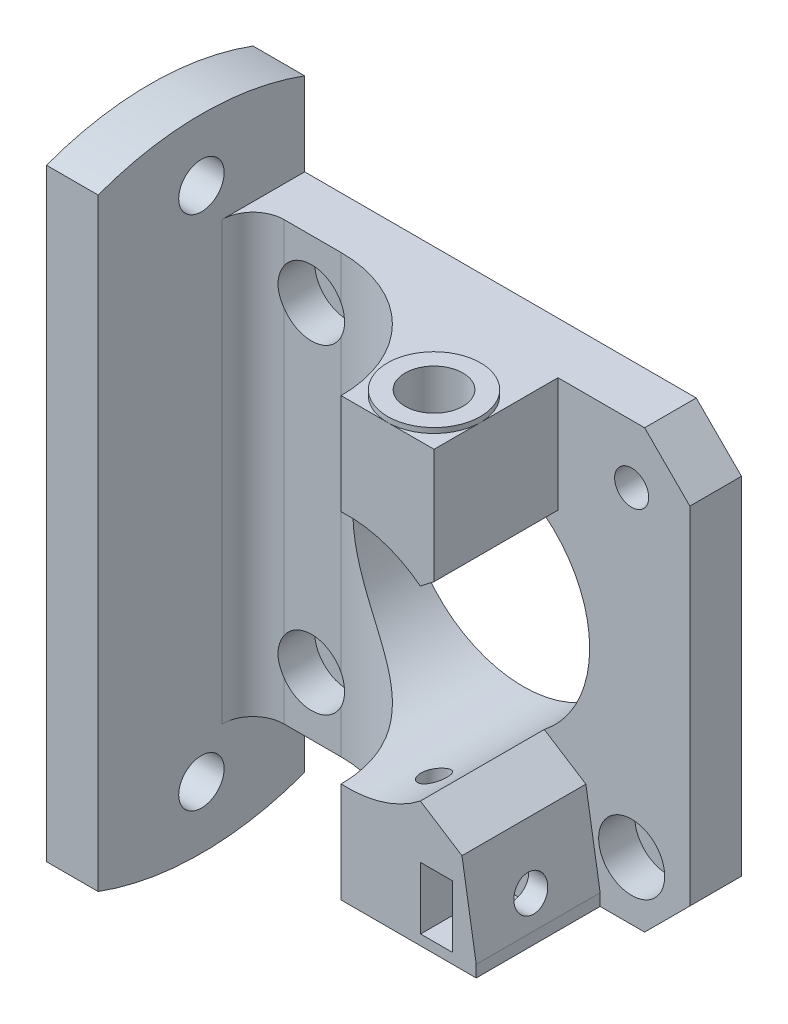
SolidWorks part; units mm, degrees
material "ABS"
ref_plane "Front Plane" through (0, 0, 0) normal (0, 0, 1) x (1, 0, 0)
ref_plane "Top Plane" through (0, 0, 0) normal (0, 1, 0) x (1, 0, 0)
ref_plane "Right Plane" through (0, 0, 0) normal (1, 0, 0) x (0, 0, -1)
sketch "Sketch1" plane through (0, 0, 0) normal (0, 0, 1) x (1, 0, 0)
  line L1 (-21.15, -21.15) -> (21.15, -21.15)
  line L2 (-21.15, -21.15) -> (-21.15, 21.15)
  line L3 (-21.15, 21.15) -> (21.15, 21.15)
  line L4 (21.15, -21.15) -> (21.15, 21.15)
  line L5 (-21.15, -21.15) -> (21.15, 21.15) construction
  line L6 (-21.15, 21.15) -> (21.15, -21.15) construction
  point P0 (0, 0)
  dimension "D1" = 42.3
extrude "Boss-Extrude1" add sketch "Sketch1" along normal blind 5
chamfer "Chamfer1" distance 4.38 angle 45 2 edges at (21.15, -21.15, 2.5) (21.15, 21.15, 2.5)
sketch "Sketch4" plane through (0, 0, 0) normal (0, 0, -1) x (-1, 0, 0)
  line L0 (21.15, 21.15) -> (21.15, -21.15) construction
  line L1 (21.15, 31) -> (26.15, 31)
  line L2 (21.15, 31) -> (21.15, -31)
  line L3 (21.15, -31) -> (26.15, -31)
  line L4 (26.15, 31) -> (26.15, -31)
  line L7 (-21.15, 0) -> (26.15, 0) construction
  line L8 (-21.15, -16.77) -> (-21.15, 16.77) construction
  dimension "D1" = 5
  dimension "D2" = 62
extrude "Boss-Extrude2" add sketch "Sketch4" against normal blind 20
sketch "Sketch5" plane through (-26.15, 0, 0) normal (-1, 0, 0) x (0, 0, 1)
  line L0 (20, -31) -> (20, 31) construction
  line L1 (20, 31) -> (0, 31) construction
  line L2 (20, -31) -> (0, -31) construction
  line L3 (0, -31) -> (0, 31) construction
  line L4 (0, 29.206) -> (0, 32.206)
  line L5 (0, 32.206) -> (20, 32.206)
  line L6 (20, 29.206) -> (20, 32.206)
  line L7 (20, 0) -> (28.987, 0) construction
  line L8 (20, -29.206) -> (20, -32.206)
  line L9 (0, -32.206) -> (20, -32.206)
  line L10 (0, -29.206) -> (0, -32.206)
  circle A0 centre (10, 25) radius 2.2
  circle A1 centre (10, -25) radius 2.2
  arc A2 (0, 29.206) -> (20, 29.206) centre (10, 2.2323) cw
  arc A3 (0, -29.206) -> (20, -29.206) centre (10, -2.2323) ccw
  dimension "D1" = 10
  dimension "D2" = 6
  dimension "D3" = 6
  dimension "D4" = 4.4
  dimension "D5" = 28.7677
  dimension "D6" = 3
extrude "Cut-Extrude3" cut sketch "Sketch5" against normal through all
sketch "Sketch6" plane through (0, -21.15, 0) normal (0, -1, 0) x (1, 0, 0)
  line L0 (12.462, 5) -> (12.462, 17)
  line L1 (-21.15, 5) -> (16.77, 5) construction
  line L2 (12.462, 17) -> (-0.624, 17)
  line L3 (-12.624, 5) -> (12.462, 5)
  line L4 (21.15, 5) -> (21.15, 0) construction
  arc A0 (-0.624, 17) -> (-12.624, 5) centre (-12.624, 17) cw
  dimension "D4" = 12
  dimension "D1" = 12
  dimension "D2" = 8.688
  dimension "D3" = 13.086
extrude "Boss-Extrude3" add sketch "Sketch6" against normal up to surface (42.3 mm away) up to face at (2.55, 21.15, 3.125)
fillet "Fillet1" radius 3 1 edges at (-21.15, 0, 5)
sketch "Sketch2" plane through (0, 0, 5) normal (0, 0, 1) x (1, 0, 0)
  line L0 (-15.4839, -15.5) -> (-15.4839, 15.5) construction
  line L1 (-15.4839, 15.5) -> (15.5161, 15.5) construction
  line L2 (15.5161, 15.5) -> (-15.4839, -15.5) construction
  line L3 (21.15, -16.77) -> (21.15, 16.77) construction
  line L4 (0.0161, 0) -> (21.15, 0) construction
  circle A0 centre (0.0161, 0) radius 11.4339
  circle A1 centre (-15.4839, 15.5) radius 1.65
  circle A2 centre (15.5161, 15.5) radius 1.65
  circle A3 centre (15.5161, -15.5) radius 1.65
  circle A4 centre (-15.4839, -15.5) radius 1.65
  dimension "D1" = 3.3
  dimension "D3" = 22.8678
  dimension "D4" = 21.1339
  dimension "D2" = 31
extrude "Cut-Extrude1" cut sketch "Sketch2" against normal through all both and the other way through all
sketch "Sketch3" plane through (0, 0, 5) normal (0, 0, 1) x (1, 0, 0)
  circle A0 centre (-15.4839, 15.5) radius 3.2
  circle A1 centre (-15.4839, -15.5) radius 3.2
  circle A2 centre (15.5161, -15.5) radius 3.2
  dimension "D1" = 6.4
extrude "Cut-Extrude2" cut sketch "Sketch3" against normal blind 3.5 and the other way through all
sketch "Sketch7" plane through (0, -21.15, 0) normal (0, -1, 0) x (1, 0, 0)
  line L0 (12.462, 5) -> (12.462, 17) construction
  line L1 (12.462, 17) -> (-0.624, 17) construction
  circle A0 centre (3.8767, 12.5) radius 1.2744
  dimension "D1" = 2.5488
  dimension "D2" = 8.5853
  dimension "D3" = 4.5
extrude "Cut-Extrude4" cut sketch "Sketch7" against normal through all
sketch "Sketch8" plane through (0, -21.15, 0) normal (0, -1, 0) x (1, 0, 0)
  circle A0 centre (3.8767, 12.5) radius 3.5
  circle A1 centre (3.8767, 12.5) radius 1.2744 construction
  circle A2 centre (3.8767, 12.5) radius 1.2744
  dimension "D1" = 7
extrude "Boss-Extrude4" add sketch "Sketch8" along normal blind 0.5
sketch "Sketch9" plane through (0, 21.15, 0) normal (0, 1, 0) x (1, 0, 0)
  circle A0 centre (3.8767, -12.5) radius 2.8
  dimension "D1" = 5.6
extrude "Cut-Extrude5" cut sketch "Sketch9" against normal blind 4
sketch "Sketch10" plane through (0, 21.15, 0) normal (0, 1, 0) x (1, 0, 0)
  circle A0 centre (3.8767, -12.5) radius 4.5
  circle A1 centre (3.8767, -12.5) radius 2.8 construction
  circle A2 centre (3.8767, -12.5) radius 2.8
  dimension "D1" = 9
extrude "Boss-Extrude5" add sketch "Sketch10" along normal blind 0.5
sketch "Sketch11" plane through (0, 0, 17) normal (0, 0, 1) x (1, 0, 0)
  line L0 (12.462, -21.15) -> (-0.624, -21.15) construction
  line L1 (7.076, -14.15) -> (10.176, -14.15)
  line L2 (7.076, -14.15) -> (7.076, -20.15)
  line L3 (7.076, -20.15) -> (10.176, -20.15)
  line L4 (10.176, -14.15) -> (10.176, -20.15)
  line L5 (21.15, -16.77) -> (21.15, 16.77) construction
  dimension "D1" = 6
  dimension "D2" = 3.1
  dimension "D3" = 1
  dimension "D4" = 10.974
extrude "Cut-Extrude6" cut sketch "Sketch11" against normal blind 7.826
sketch "Sketch12" plane through (7.076, 0, 0) normal (1, 0, 0) x (0, 0, -1)
  line L0 (-16, -21.65) -> (-9, -21.65) construction
  line L1 (-17, -16.4552) -> (-17, -21.15) construction
  circle A0 centre (-11.25, -17.15) radius 1.62
  dimension "D1" = 3.24
  dimension "D2" = 4.5
  dimension "D3" = 5.75
extrude "Cut-Extrude7" cut sketch "Sketch12" against normal blind 0.45 and the other way through all
sketch "Sketch13" plane through (0, 0, 17) normal (0, 0, 1) x (1, 0, 0)
  line L0 (12.462, 21.15) -> (8.3767, 21.15)
  line L1 (3.8767, 21.15) -> (12.462, 21.15) construction
  line L2 (8.3767, 21.15) -> (8.3767, 10.042)
  line L3 (7.052, -9.0128) -> (11.082, -11.582)
  line L4 (11.082, -11.582) -> (12.462, -20)
  line L6 (12.462, -20) -> (12.462, 21.15)
  line L7 (8.3767, 10.042) -> (7.0527, 9.0122)
  line L8 (12.462, -16.4552) -> (12.462, -21.15) construction
  line L9 (12.462, -21.15) -> (16.77, -21.15) construction
  line L10 (21.15, -16.77) -> (21.15, 16.77) construction
  line L11 (12.462, -21.15) -> (-0.624, -21.15) construction
  arc A0 (-0.624, -11.416) -> (-0.624, 11.416) centre (0.0161, 0) ccw construction
  arc A1 (7.052, -9.0128) -> (7.0527, 9.0122) centre (0.0161, 0) ccw
  dimension "D1" = 11.108
  dimension "D2" = 1.324
  dimension "D3" = 1.15
  dimension "D4" = 10.068
  dimension "D5" = 9.568
  dimension "D6" = 14.098
extrude "Cut-Extrude8" cut sketch "Sketch13" against normal up to surface (12 mm away) up to face at (16.4928, -3.875, 5)
